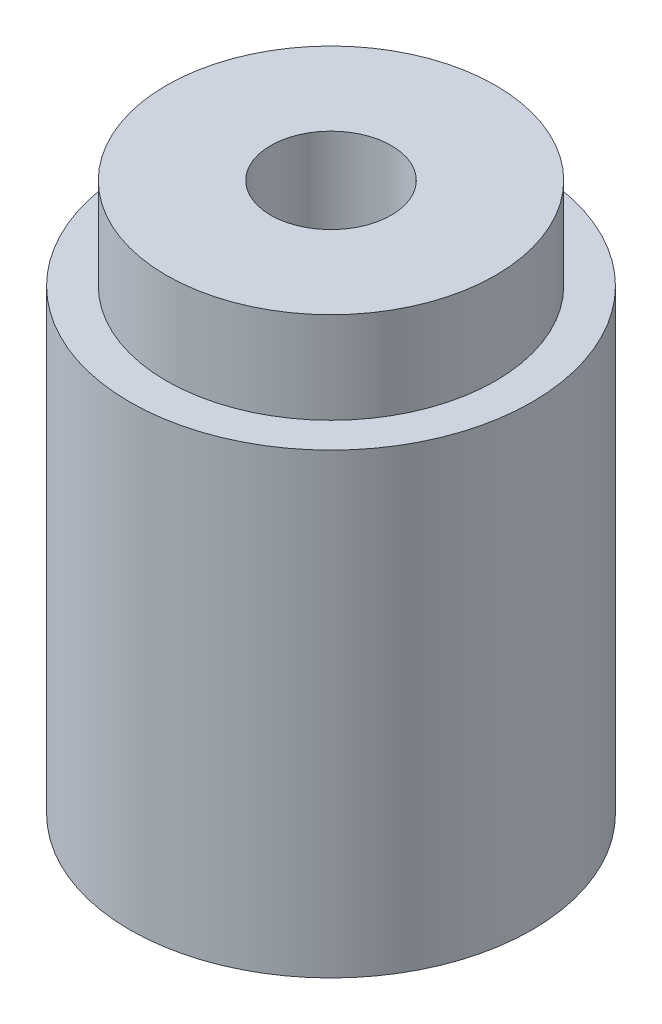
SolidWorks part; units mm, degrees
material "AISI 1015 Steel, Cold Drawn (SS)"
ref_plane "Front Plane" through (0, 0, 0) normal (0, 0, 1) x (1, 0, 0)
ref_plane "Top Plane" through (0, 0, 0) normal (0, 1, 0) x (1, 0, 0)
ref_plane "Right Plane" through (0, 0, 0) normal (1, 0, 0) x (0, 0, -1)
sketch "Sketch1" plane through (0, 0, 0) normal (0, 0, 1) x (1, 0, 0)
  line L0 (0, 18.8279) -> (0, -17.5681) construction
  line L1 (3.3, 30) -> (9, 30)
  line L2 (9, 30) -> (9, 25)
  line L3 (9, 25) -> (11, 25)
  line L4 (11, 25) -> (11, 0)
  line L5 (11, 0) -> (8, 0)
  line L6 (8, 0) -> (8, 23)
  line L7 (8, 23) -> (3.3, 23)
  line L8 (3.3, 23) -> (3.3, 30)
  dimension "D1" = 3.3
  dimension "D2" = 8
  dimension "D3" = 11
  dimension "D4" = 7
  dimension "D5" = 30
  dimension "D6" = 25
  dimension "D7" = 9
revolve "Revolve1" add sketch "Sketch1" angle 360 about L0
cosmetic thread "Cosmetic Thread1"
cosmetic thread "Cosmetic Thread2"
